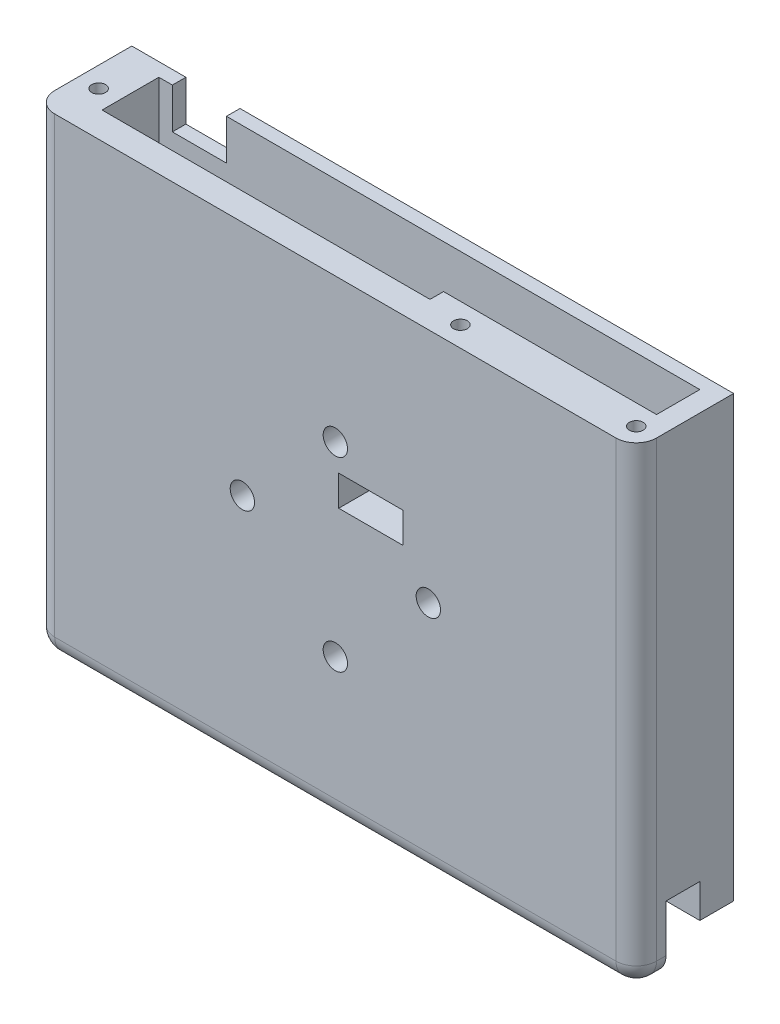
SolidWorks part; units mm, degrees
ref_plane "Front Plane" through (0, 0, 0) normal (0, 0, 1) x (1, 0, 0)
ref_plane "Top Plane" through (0, 0, 0) normal (0, 1, 0) x (1, 0, 0)
ref_plane "Right Plane" through (0, 0, 0) normal (1, 0, 0) x (0, 0, -1)
sketch "Sketch1" plane through (0, 0, 0) normal (0, 0, 1) x (1, 0, 0)
  line L5 (-38.5, 35) -> (41.5, 35)
  line L6 (-38.5, 35) -> (-38.5, -15)
  line L7 (-44.5, 35) -> (44.5, 35)
  line L8 (-44.5, 35) -> (-44.5, -35)
  line L9 (-44.5, -35) -> (44.5, -35)
  line L10 (44.5, 35) -> (44.5, -35)
  line L11 (-44.5, 35) -> (44.5, -35) construction
  line L12 (-44.5, -35) -> (44.5, 35) construction
  line L13 (-38.5, -15) -> (41.5, -15)
  line L14 (41.5, 35) -> (41.5, -15)
  point P0 (0, 0)
  point P5 (0, 0)
  dimension "D1" = 50
  dimension "D2" = 80
  dimension "D3" = 89
  dimension "D4" = 70
  dimension "D5" = 6
extrude "Boss-Extrude1" add sketch "Sketch1" along normal blind 6.4 contours L7 L14 L13 L6 L8 L9 L10
sketch "Sketch2" plane through (0, 0, 0) normal (0, 0, -1) x (-1, 0, 0)
  line L6 (-44.5, 35) -> (44.5, 35)
  line L7 (-44.5, 35) -> (-44.5, -35)
  line L8 (-44.5, -35) -> (44.5, -35)
  line L9 (44.5, 35) -> (44.5, -35)
extrude "Boss-Extrude2" add sketch "Sketch2" along normal blind 2
sketch "Sketch3" plane through (0, 0, 0) normal (0, 0, 1) x (1, 0, 0)
  line L1 (-36.5, 35) -> (-28.5, 35)
  line L2 (-36.5, 35) -> (-36.5, 29)
  line L3 (-36.5, 29) -> (-28.5, 29)
  line L4 (-28.5, 35) -> (-28.5, 29)
  line L6 (-38.5, 35) -> (-38.5, -15) construction
  line L7 (-38.5, 35) -> (41.5, 35) construction
  dimension "D1" = 8
  dimension "D2" = 6
  dimension "D3" = 2
extrude "Cut-Extrude1" cut sketch "Sketch3" against normal up to surface (2 mm away) up to face at (0, 0, -2)
sketch "Sketch5" plane through (0, 0, 6.4) normal (0, 0, 1) x (1, 0, 0)
  line L1 (-44.5, 35) -> (44.5, 35)
  line L2 (-44.5, 35) -> (-44.5, -35)
  line L3 (-44.5, -35) -> (44.5, -35)
  line L4 (44.5, 35) -> (44.5, -35)
extrude "Boss-Extrude3" add sketch "Sketch5" along normal blind 6
hole_wizard "CBORE for M3 SHCS1" positions "Sketch6" profile "Sketch7" counterbore size "M3" standard "ANSI Metric" end condition through all
sketch "Sketch6" plane through (0, 0, -2) normal (0, 0, -1) x (-1, 0, 0)
  line L0 (-13.75, 0) -> (0, 0) construction
  line L1 (0, 0) -> (13.75, 0) construction
  line L3 (0, 13.75) -> (0, 0) construction
  line L5 (0, 0) -> (0, -13.75) construction
  point P0 (0, -13.75)
  point P2 (0, 13.75)
  point P4 (-13.75, 0)
  point P6 (13.75, 0)
  dimension "D1" = 13.75
sketch "Sketch7" plane through (0, -13.75, -2) normal (1, 0, 0) x (0, 1, 0)
  line L0 (0, 0) -> (0, 14.4)
  line L1 (0, 14.4) -> (1.8, 14.4)
  line L3 (1.8, 14.4) -> (1.8, 11.5)
  line L4 (1.8, 11.5) -> (3.5, 11.5)
  line L5 (3.5, 11.5) -> (3.5, 0)
  line L7 (3.5, 0) -> (0, 0)
  line L11 (0, -6.35) -> (0, 107.95) construction
  dimension "Thru Hole Dia." = 3.6
  dimension "Thru Hole Depth" = 14.4
  dimension "C'Bore Dia." = 7
  dimension "C'Bore Depth" = 11.5
sketch "Sketch8" plane through (0, 0, 12.4) normal (0, 0, 1) x (1, 0, 0)
  line L1 (0.5, 10) -> (10, 10)
  line L2 (0.5, 10) -> (0.5, 5.5)
  line L3 (0.5, 5.5) -> (10, 5.5)
  line L4 (10, 10) -> (10, 5.5)
  circle A0 centre (0, 13.75) radius 1.8 construction
  circle A1 centre (13.75, 0) radius 1.8 construction
  dimension "D3" = 3.75
  dimension "D4" = 3.75
  dimension "D1" = 9.5
  dimension "D2" = 4.5
extrude "Cut-Extrude3" cut sketch "Sketch8" against normal up to surface (6 mm away) up to face at (3.5, 13.75, 6.4)
sketch "Sketch10" plane through (0, 0, 6.4) normal (0, 0, -1) x (-1, 0, 0)
  line L0 (-10, 10) -> (5, 10)
  line L1 (-10, 10) -> (-10, 35)
  line L2 (5, 10) -> (5, 35)
  line L3 (-10, 35) -> (5, 35)
  line L4 (-41.5, 35) -> (38.5, 35) construction
  line L5 (38.5, 35) -> (38.5, -15) construction
  line L6 (5, 35) -> (38.5, 35)
  line L7 (5, 35) -> (5, 30)
  line L8 (5, 30) -> (38.5, 30)
  line L9 (38.5, 35) -> (38.5, 30)
  line M5 (-10, 10) -> (-0.5, 10)
  line M13 (38.5, 35) -> (-41.5, 35)
  line M16 (38.5, -15) -> (38.5, 35)
  dimension "D1" = 15
  dimension "D2" = 5
extrude "Cut-Extrude4" cut sketch "Sketch10" against normal blind 2 contours L2 L8 M16 M13 | L2 L1 M5 M13
hole_wizard "M2.5x0.45 Tapped Hole1" positions "Sketch11" profile "Sketch12" tap size "M2.5x0.45" standard "ANSI Metric"
sketch "Sketch11" plane through (0, 35, 0) normal (0, 1, 0) x (1, 0, 0)
  line L5 (-44.5, -12.4) -> (-44.5, 2) construction
  line L6 (44.5, -12.4) -> (44.5, 2) construction
  line L7 (44.5, -12.4) -> (-44.5, -12.4) construction
  point P0 (-41.5, -5.9)
  point P2 (41.5, -9.4)
  point P7 (15.5, -9.4)
  dimension "D1" = 6.5
  dimension "D2" = 3
  dimension "D3" = 3
  dimension "D4" = 3
  dimension "D5" = 3
  dimension "D6" = 29
sketch "Sketch12" plane through (-41.5, 35, 5.9) normal (1, 0, 0) x (0, 0, 1)
  line L0 (0, 0) -> (0, 7.8659)
  line L1 (0, 7.8659) -> (1.025, 7.25)
  line L2 (1.025, 7.25) -> (1.025, 0)
  line L5 (1.025, 0) -> (0, 0)
  line L10 (0, 7.8659) -> (-1.025, 7.25) construction
  line L11 (0, -6.35) -> (0, 107.95) construction
  dimension "Tap Drill Dia." = 2.05
  dimension "Tap Drill Depth" = 7.25
  dimension "Drill Angle" = 118
cosmetic thread "Hole Thread1" parameters "D1"=5, "D2"=2.5
cosmetic thread "Hole Thread2" parameters "D1"=5, "D2"=2.5
cosmetic thread "Hole Thread3" parameters "D1"=5, "D2"=2.5
sketch "Sketch13" plane through (-44.5, 0, 0) normal (-1, 0, 0) x (0, 0, 1)
  line L0 (-2, -35) -> (8, -35)
  line L1 (12.4, -35) -> (-2, -35) construction
  line L2 (8, -35) -> (8, -25)
  line L3 (8, -25) -> (3, -25)
  line L4 (3, -25) -> (3, -30)
  line L5 (3, -30) -> (-2, -30)
  line L6 (-2, -35) -> (-2, 35) construction
  line L7 (-2, -30) -> (-2, -35)
  dimension "D2" = 10
  dimension "D1" = 10
  dimension "D3" = 5
  dimension "D4" = 5
extrude "Cut-Extrude5" cut sketch "Sketch13" against normal through all
fillet "Fillet1" radius 3 5 edges at (-44.5, -35, 10.2) (-44.5, 0, 12.4) (0, -35, 12.4) (44.5, 0, 12.4) (44.5, -35, 10.2)
